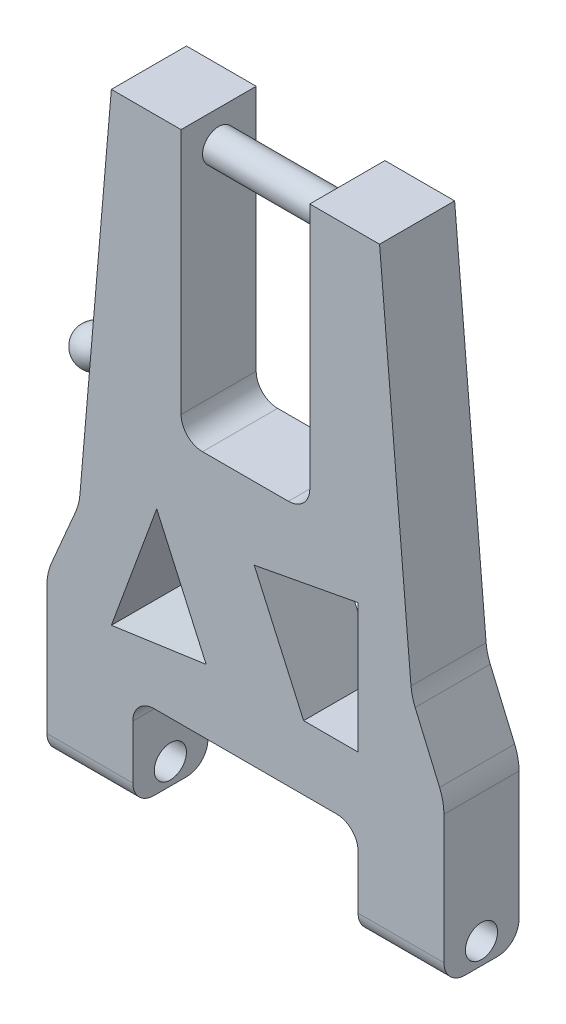
SolidWorks part; units mm, degrees
ref_plane "前视基准面" through (0, 0, 0) normal (0, 0, 1) x (1, 0, 0)
ref_plane "上视基准面" through (0, 0, 0) normal (0, 1, 0) x (1, 0, 0)
ref_plane "右视基准面" through (0, 0, 0) normal (1, 0, 0) x (0, 0, -1)
sketch "草图1" plane through (0, 0, 0) normal (0, 0, 1) x (1, 0, 0)
  line L0 (0, 0) -> (8, 0)
  line L1 (0, 0) -> (0, 13.9737)
  line L2 (29, 0) -> (37, 0)
  line L4 (2.6828, 21.2598) -> (0.4043, 15.9433)
  line L6 (37, 0) -> (37, 13.9737)
  line L9 (34.3172, 21.2598) -> (36.5957, 15.9433)
  line L11 (6, 57) -> (3.0688, 22.8024)
  line L12 (6, 57) -> (31, 57)
  line L15 (31, 57) -> (33.9312, 22.8024)
  line L16 (6, 57) -> (18.5, 57)
  line L17 (18.5, 57) -> (18.5, 32)
  line L18 (18.5, 32) -> (14.5, 32)
  line L19 (12.5, 32) -> (22.5, 32)
  line L20 (24.5, 34) -> (24.5, 57)
  line L21 (24.5, 57) -> (12.5, 57)
  line L22 (12.5, 57) -> (12.5, 34)
  line L23 (0, 0) -> (8, 0)
  line L24 (8, 0) -> (8, 7)
  line L25 (37, 0) -> (29, 0)
  line L26 (29, 0) -> (29, 7)
  line L27 (27, 9) -> (10, 9)
  line L28 (10.2294, 25.2482) -> (6, 13.7362)
  line L29 (6, 13.7362) -> (14.8342, 15)
  line L30 (14.8342, 15) -> (10.2294, 25.2482)
  line L31 (19.3178, 25.2482) -> (23.9226, 15)
  line L32 (23.9226, 15) -> (29, 15)
  line L33 (29, 15) -> (29, 27.0659)
  line L34 (29, 27.0659) -> (19.3178, 25.2482)
  arc A0 (2.6828, 21.2598) -> (3.0688, 22.8024) centre (-1.913, 23.2294) ccw
  arc A1 (0, 13.9737) -> (0.4043, 15.9433) centre (5, 13.9737) cw
  arc A2 (33.9312, 22.8024) -> (34.3172, 21.2598) centre (38.913, 23.2294) ccw
  arc A3 (36.5957, 15.9433) -> (37, 13.9737) centre (32, 13.9737) cw
  arc A4 (12.5, 34) -> (14.5, 32) centre (14.5, 34) ccw
  arc A5 (22.5, 32) -> (24.5, 34) centre (22.5, 34) ccw
  arc A6 (29, 7) -> (27, 9) centre (27, 7) ccw
  arc A7 (10, 9) -> (8, 7) centre (10, 7) ccw
  dimension "D1" = 5
  dimension "D2" = 5
  dimension "D3" = 5
  dimension "D4" = 5
  dimension "D5" = 2
  dimension "D6" = 2
  dimension "D7" = 2
  dimension "D8" = 2
extrude "凸台-拉伸1" add sketch "草图1" along normal blind 7
sketch "草图2" plane through (8, 0, 0) normal (1, 0, 0) x (0, 0, -1)
  line L0 (-7, 0) -> (-7, 7) construction
  line L1 (-7, 0) -> (0, 0) construction
  circle A0 centre (-3.5, 2) radius 1.5
  dimension "D1" = 3.5
  dimension "D2" = 2
extrude "切除-拉伸1" cut sketch "草图2" against normal mid plane 100
sketch "草图3" plane through (12.5, 0, 0) normal (1, 0, 0) x (0, 0, -1)
  line L0 (-7, 57) -> (-7, 34) construction
  line L1 (-7, 57) -> (0, 57) construction
  circle A0 centre (-3.5, 54) radius 1.5
  dimension "D1" = 3
  dimension "D2" = 3.5
  dimension "D3" = 3
ref_plane "基准面1" through (3, 0, 0) normal (-1, 0, 0) x (0, 0, 1)
sketch "草图5" plane through (3, 0, 0) normal (-1, 0, 0) x (0, 0, 1)
  line L0 (0, 0) -> (3.5, 0)
  line L1 (3.5, 0) -> (3.5, 32)
  circle A0 centre (3.5, 32) radius 2
extrude "凸台-拉伸2" add sketch "草图5" against normal blind 2
ref_plane "基准面2" through (0, 0, 3.5) normal (0, 0, -1) x (-1, 0, 0)
sketch "草图6" plane through (0, 0, 3.5) normal (0, 0, -1) x (-1, 0, 0)
  line L0 (0, 0) -> (-3, 0)
  line L1 (-3, 0) -> (-3, 32)
  line L2 (-3, 32) -> (-1, 32)
  line L3 (-1, 32) -> (0.75, 32)
  line L4 (-3, 32) -> (-3, 30)
  line L5 (-3, 30) -> (-2.2374, 30.7626)
  arc A0 (-2.2374, 30.7626) -> (0.75, 32) centre (-1, 32) ccw
revolve "旋转1" add sketch "草图6" angle 360 about L2
fillet "圆角2" radius 2 4 edges at (33, 0, 7) (33, 0, 0) (4, 0, 0) (4, 0, 7)
extrude "凸台-拉伸3" add sketch "草图3" along normal blind 12
